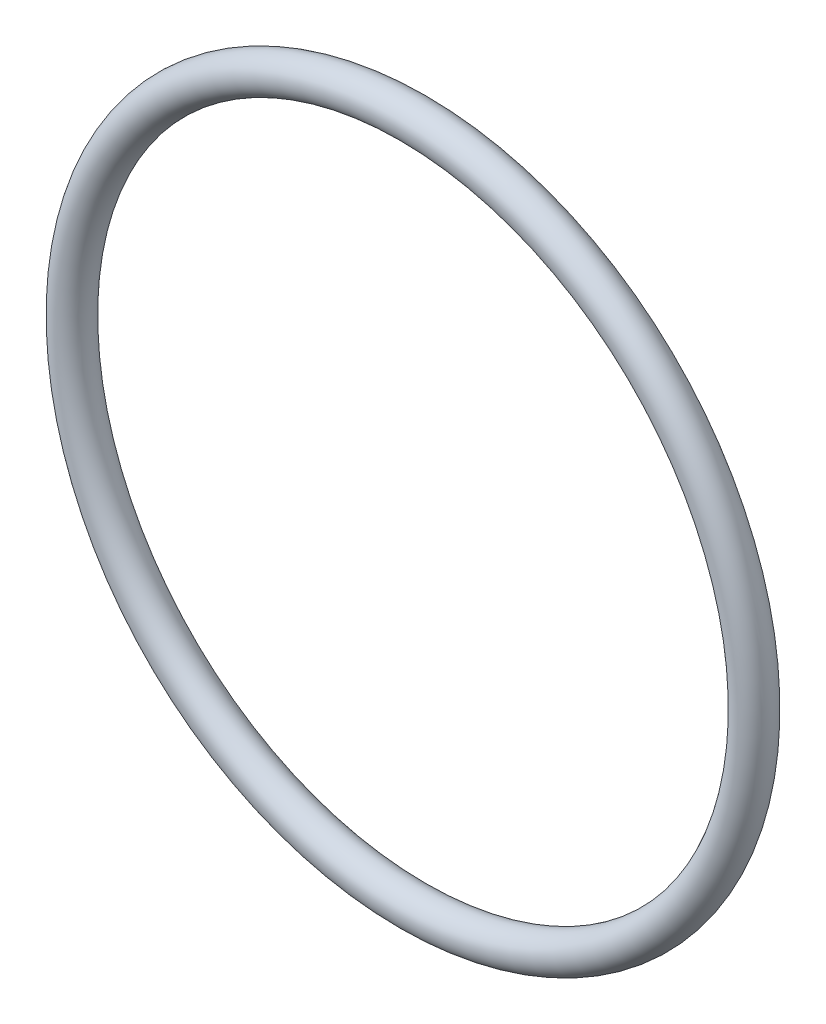
SolidWorks part; units mm, degrees
material "Silicon"
ref_plane "Front Plane" through (0, 0, 0) normal (0, 0, 1) x (1, 0, 0)
ref_plane "Top Plane" through (0, 0, 0) normal (0, 1, 0) x (1, 0, 0)
ref_plane "Right Plane" through (0, 0, 0) normal (1, 0, 0) x (0, 0, -1)
sketch "Sketch1" plane through (0, 0, 0) normal (1, 0, 0) x (0, 0, -1)
  line L0 (0, -15.7353) -> (0, 15.7353) construction
  circle A0 centre (0, -16.6243) radius 0.889 construction
  circle A1 centre (0, 16.6243) radius 0.889 construction
  point P3 (-0.889, -15.7353)
  point P4 (0, 0)
  point P7 (0, -17.5133)
  point P8 (-0.889, -16.6243)
  point P9 (0.889, -16.6243)
  point P12 (0, 17.5133)
  dimension "ID" = 31.4706
  dimension "OD" = 35.0266
  dimension "Width" = 1.778
sketch "Sketch2" plane through (0, 0, 0) normal (1, 0, 0) x (0, 0, -1)
  line L0 (-15.7353, 0) -> (15.7353, 0)
  line L1 (0, -15.7353) -> (0, 15.7353) construction
  circle A0 centre (0, 16.6243) radius 0.889 construction
  circle A1 centre (0, 16.6243) radius 0.889
  point P6 (0, 0)
  point P7 (0, 0)
revolve "Revolve1" add sketch "Sketch2" angle 360 about L0
sketch "Drawing Reference 1" plane through (0, 0, 0) normal (0, 0, 1) x (1, 0, 0)
  circle A0 centre (0, 0) radius 17.5133
  circle A1 centre (0, 0) radius 15.7353
